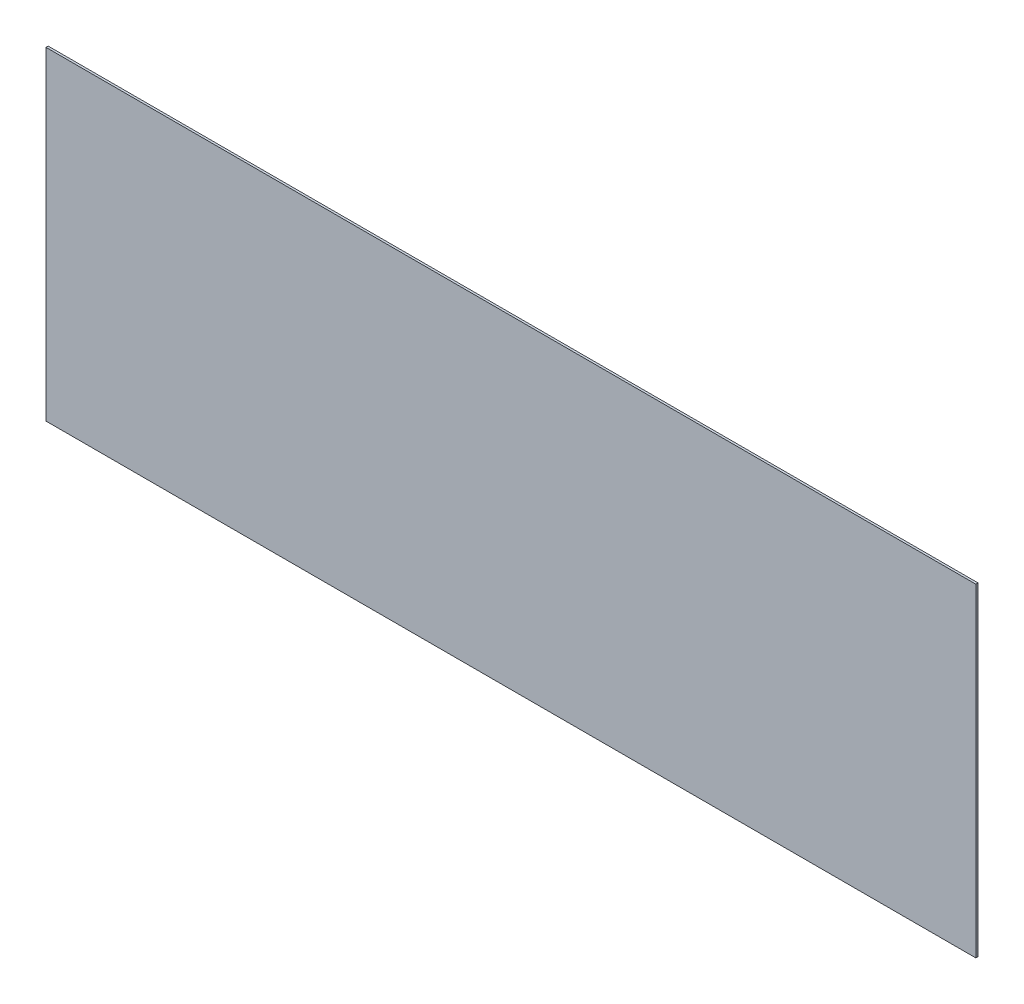
SolidWorks part; units mm, degrees
material "Chrome Stainless Steel"
ref_plane "Front Plane" through (0, 0, 0) normal (0, 0, 1) x (1, 0, 0)
ref_plane "Top Plane" through (0, 0, 0) normal (0, 1, 0) x (1, 0, 0)
ref_plane "Right Plane" through (0, 0, 0) normal (1, 0, 0) x (0, 0, -1)
sketch "Sketch1" plane through (0, 0, 0) normal (0, 0, 1) x (1, 0, 0)
  line L1 (325.1415, 0) -> (747.4, 0)
  line L2 (325.1415, 0) -> (325.1415, 147)
  line L3 (325.1415, 147) -> (747.4, 147)
  line L4 (747.4, 0) -> (747.4, 147)
extrude "Boss-Extrude1" add sketch "Sketch1" along normal blind 1
